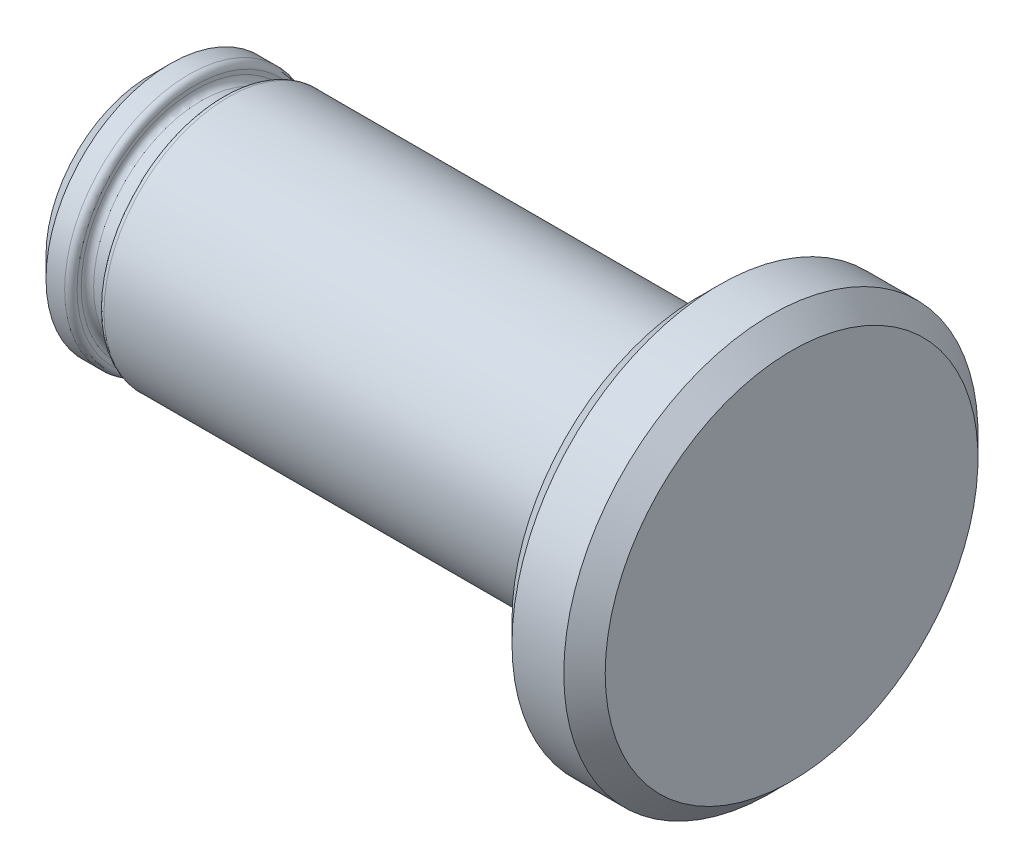
SolidWorks part; units mm, degrees
material "ABS"
ref_plane "Front Plane" through (0, 0, 0) normal (1, 0, 0) x (0, 1, 0)
ref_plane "Top Plane" through (0, 0, 0) normal (0, 0, 1) x (0, 1, 0)
ref_plane "Right Plane" through (0, 0, 0) normal (0, 1, 0) x (-1, 0, 0)
sketch "Sketch1" plane through (0, 0, 0) normal (0, 1, 0) x (-1, 0, 0)
  line L0 (0, 0) -> (0, 10) construction
  line L1 (-1, 10) -> (-3.5, 10)
  line L2 (-4.5, 9) -> (-4.5, 0)
  line L3 (-4.5, 0) -> (26.5, 0) construction
  line L4 (26.5, 0) -> (26.5, 5)
  line L5 (25.5, 6) -> (24.6, 6)
  line L6 (0, 9) -> (0, 8)
  line L7 (24.3, 5.7) -> (24.3, 5.5)
  line L8 (24, 5.2) -> (23.3, 5.2)
  line L9 (23, 5.5) -> (23, 5.7)
  line L10 (22.7, 6) -> (2, 6)
  line L11 (26.5, 5) -> (25.5, 6)
  line L12 (-1, 10) -> (0, 9)
  line L13 (-3.5, 10) -> (-4.5, 9)
  line L14 (26.5, 0) -> (-4.5, 0)
  arc A0 (2, 6) -> (0, 8) centre (2, 8) cw
  arc A1 (24.3, 5.7) -> (24.6, 6) centre (24.6, 5.7) cw
  arc A2 (24.3, 5.5) -> (24, 5.2) centre (24, 5.5) cw
  arc A3 (23.3, 5.2) -> (23, 5.5) centre (23.3, 5.5) cw
  arc A4 (23, 5.7) -> (22.7, 6) centre (22.7, 5.7) ccw
  point P4 (-4.5, 10)
  point P7 (26.5, 6)
  point P20 (0, 6)
  point P25 (24.3, 5.2)
  point P28 (23, 5.2)
  point P31 (23, 6)
  dimension "D8" = 2
  dimension "D9" = 0.3
  dimension "D1" = 12
  dimension "D2" = 20
  dimension "D3" = 4.5
  dimension "D4" = 3.5
  dimension "D5" = 0.8
  dimension "D6" = 23
  dimension "D7" = 1.3
revolve "Revolve1" add sketch "Sketch1" angle 360 about L14
